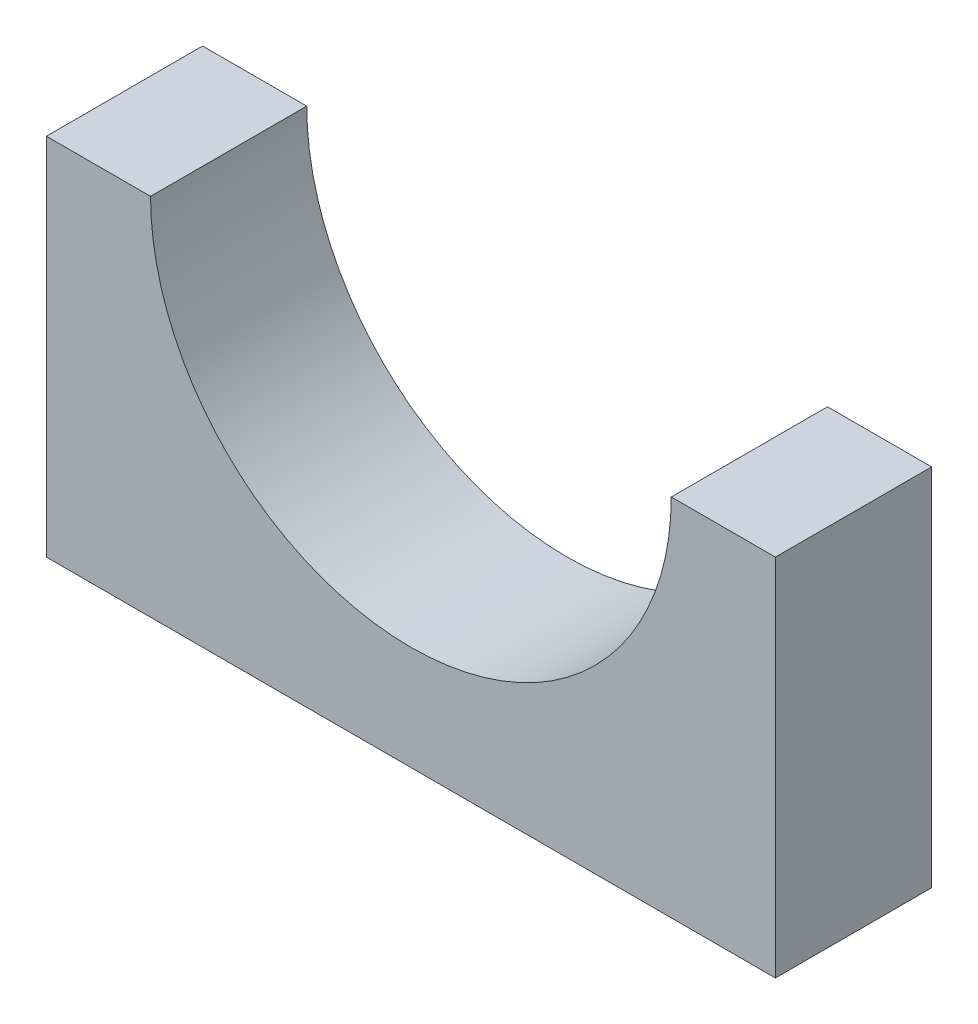
SolidWorks part; units mm, degrees
ref_plane "Front Plane" through (0, 0, 0) normal (0, 0, 1) x (1, 0, 0)
ref_plane "Top Plane" through (0, 0, 0) normal (0, 1, 0) x (1, 0, 0)
ref_plane "Right Plane" through (0, 0, 0) normal (1, 0, 0) x (0, 0, -1)
sketch "Sketch1" plane through (0, 0, 0) normal (0, 0, 1) x (1, 0, 0)
  line L0 (-17.5, 0) -> (17.5, 0)
  line L1 (17.5, 0) -> (17.5, 17.5)
  line L2 (17.5, 17.5) -> (12.5, 17.5)
  line L3 (-17.5, 0) -> (-17.5, 17.5)
  line L4 (-17.5, 17.5) -> (-12.5, 17.5)
  arc A0 (-12.5, 17.5) -> (12.5, 17.5) centre (0, 17.5) ccw
  point P3 (0, 0)
  point P4 (0, 0)
  point P10 (0, 0)
  point P11 (0, 5)
  dimension "D1" = 25
  dimension "D2" = 5
  dimension "D3" = 5
extrude "Boss-Extrude1" add sketch "Sketch1" along normal blind 7.5
